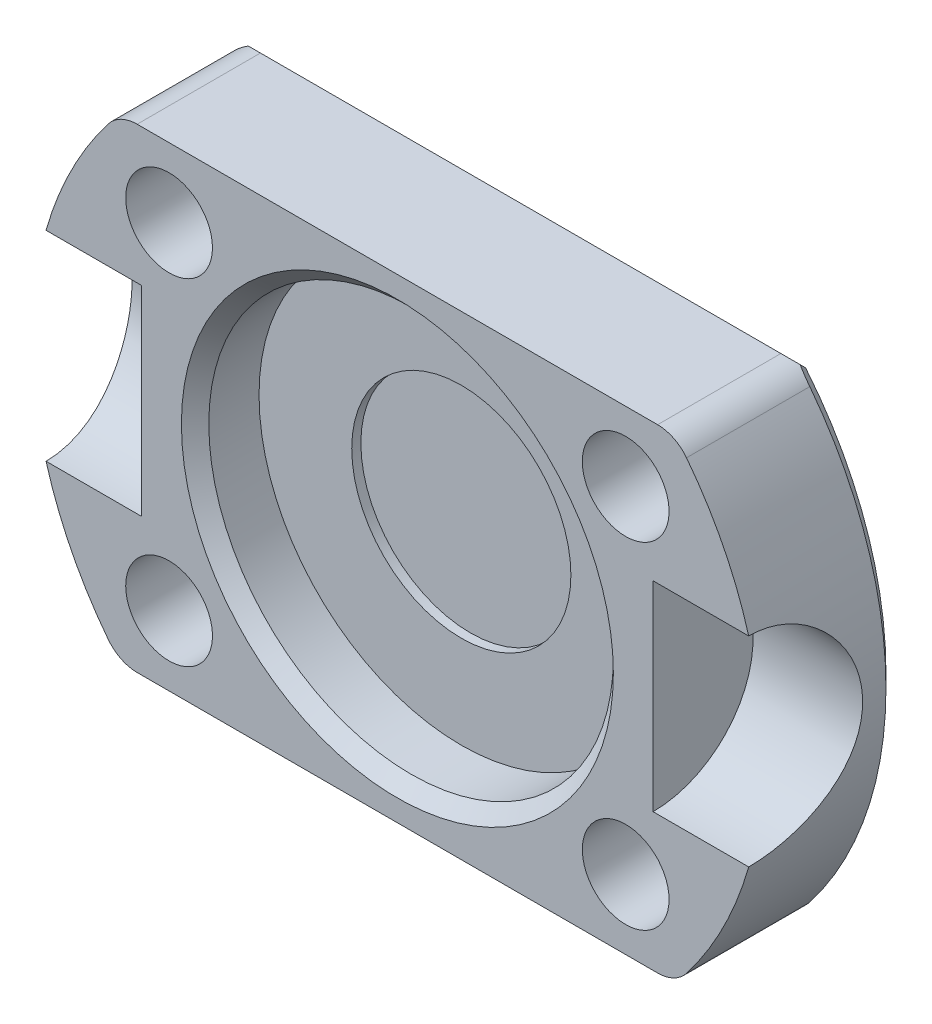
SolidWorks part; units mm, degrees
ref_plane "Front" through (0, 0, 0) normal (0, 0, 1) x (1, 0, 0)
ref_plane "Top" through (0, 0, 0) normal (0, 1, 0) x (1, 0, 0)
ref_plane "Right" through (0, 0, 0) normal (1, 0, 0) x (0, 0, -1)
sketch "Skizze1" plane through (0, 0, 0) normal (0, 0, 1) x (1, 0, 0)
  line L0 (-15.1987, 13) -> (15.1987, 13)
  line L1 (0, 0) -> (17.4858, 0) construction
  line L2 (-15.1987, -13) -> (15.1987, -13)
  arc A0 (-15.1987, 13) -> (-15.1987, -13) centre (0, 0) ccw
  arc A1 (15.1987, -13) -> (15.1987, 13) centre (0, 0) ccw
  dimension "D1" = 40
  dimension "D2" = 26
extrude "Aufsatz-Linear austragen1" add sketch "Skizze1" along normal blind 7.5
sketch "Skizze2" plane through (0, 0, 7.5) normal (0, 0, 1) x (1, 0, 0)
  circle A0 centre (0, 0) radius 11.075
  dimension "D1" = 22.15
extrude "Schnitt-Linear austragen1" cut sketch "Skizze2" against normal blind 3.5
ref_plane "Ebene1" through (14, 0, 0) normal (1, 0, 0) x (0, 0, -1)
sketch "Skizze3" plane through (14, 0, 0) normal (1, 0, 0) x (0, 0, -1)
  line L0 (-7.5, 13) -> (-7.5, -13) construction
  circle A0 centre (-7.5, 0) radius 5.475
  dimension "D1" = 10.95
extrude "Schnitt-Linear austragen2" cut sketch "Skizze3" along normal through all
mirror "Spiegeln1" about plane through (0, 0, 0) normal (1, 0, 0) of "Schnitt-Linear austragen2"
sketch "Skizze4" plane through (0, 0, 7.5) normal (0, 0, 1) x (1, 0, 0)
  line L0 (0, 0) -> (-16.1076, 11.8552) construction
  line L1 (0, 0) -> (-24.3212, 0) construction
  line L2 (0, 0) -> (0, 15.1169) construction
  circle A0 centre (-12.5, 9.2) radius 2.375
  arc A1 (-15.1987, 13) -> (-19.236, 5.475) centre (0, 0) ccw construction
  circle A2 centre (12.5, 9.2) radius 2.375
  circle A3 centre (12.5, -9.2) radius 2.375
  circle A4 centre (-12.5, -9.2) radius 2.375
  dimension "D1" = 4.75
  dimension "D2" = 12.5
  dimension "D3" = 9.2
extrude "Schnitt-Linear austragen3" cut sketch "Skizze4" against normal blind 6
chamfer "Fase1" distance 0.75 angle 45 5 edges at (0, -13, 0) (20, 0, 0) (0, 13, 0) (-20, 0, 0) (11.075, 0, 7.5)
fillet "Verrundung1" radius 2 4 edges at (-15.1987, -13, 4.125) (15.1987, -13, 4.125) (15.1987, 13, 4.125) (-15.1987, 13, 4.125)
sketch "Skizze5" plane through (0, 0, 4) normal (0, 0, 1) x (1, 0, 0)
  circle A0 centre (0, 0) radius 6
  dimension "D1" = 12
extrude "Schnitt-Linear austragen4" cut sketch "Skizze5" against normal blind 0.5
